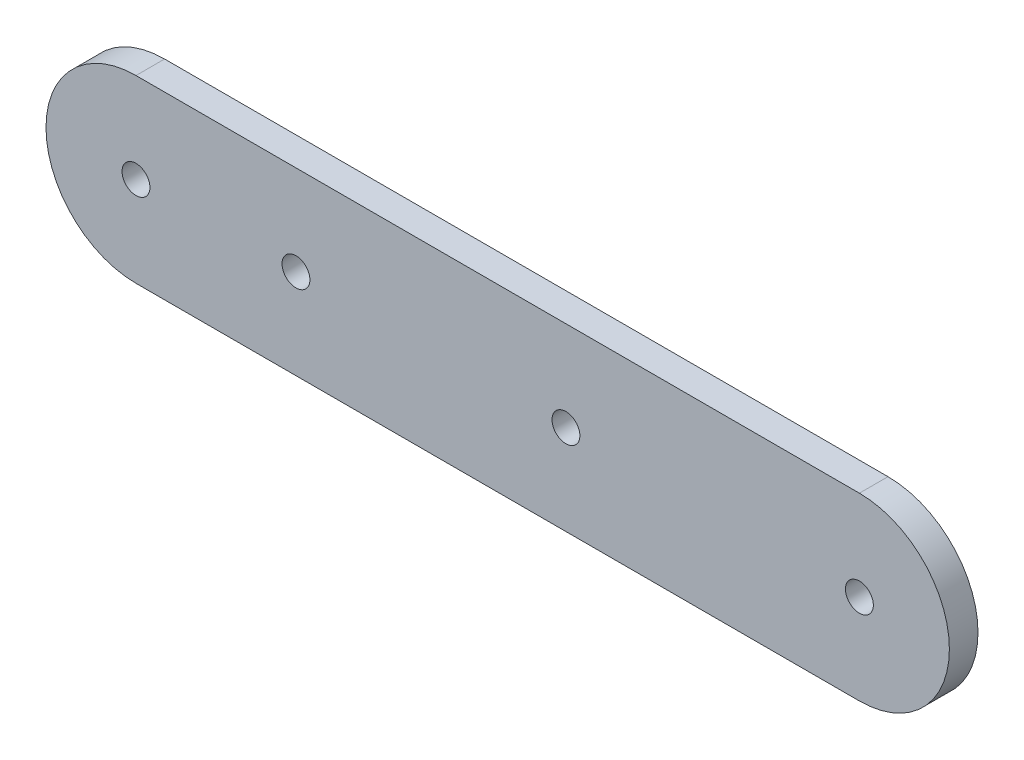
SolidWorks part; units mm, degrees
ref_plane "Front Plane" through (0, 0, 0) normal (0, 0, 1) x (1, 0, 0)
ref_plane "Top Plane" through (0, 0, 0) normal (0, 1, 0) x (1, 0, 0)
ref_plane "Right Plane" through (0, 0, 0) normal (1, 0, 0) x (0, 0, -1)
sketch "Sketch1" plane through (0, 0, 0) normal (0, 0, 1) x (1, 0, 0)
  line L0 (-34.978, 0) -> (34.978, 0) construction
  line L1 (-34.978, 10) -> (45.412, 10)
  line L2 (-34.978, -10) -> (45.412, -10)
  line L3 (45.412, -10) -> (45.412, 10) construction
  arc A0 (-34.978, 10) -> (-34.978, -10) centre (-34.978, 0) ccw
  arc A2 (45.412, -10) -> (45.412, 10) centre (0, 0) ccw
  point P2 (0, 0)
  dimension "D2" = 80.39
  dimension "D3" = 46.5
  dimension "D4" = 10
  dimension "D1" = 20
extrude "Boss-Extrude1" add sketch "Sketch1" along normal mid plane 3.18
sketch "Sketch6" plane through (0, 0, -1.59) normal (0, 0, -1) x (-1, 0, 0)
  line L0 (0, 0) -> (-23.3899, 0) construction
  circle A0 centre (-12.8, 0) radius 1.55
  arc A1 (-45.412, 10) -> (-45.412, -10) centre (0, 0) ccw construction
  dimension "D1" = 3.1
  dimension "D2" = 12.8
extrude "Cut-Extrude3" cut sketch "Sketch6" against normal through all and the other way through all
pattern_linear "LPattern3" count 3 spacing 30 along (-1, 0, 0) of "Cut-Extrude3"
sketch "Sketch7" plane through (0, 0, 1.59) normal (0, 0, 1) x (1, 0, 0)
  line L0 (0, 0) -> (57.5543, 0) construction
  line L1 (29.8, 0) -> (29.8, 14.5305) construction
  circle A1 centre (29.8, 3.5) radius 0.95
  circle A2 centre (29.8, -3.5) radius 0.95
  circle A3 centre (29.8, 0) radius 0.95
  circle A4 centre (12.8, 0) radius 1.55 construction
  dimension "D1" = 17
  dimension "D2" = 1.9
  dimension "D3" = 7
extrude "Cut-Extrude4" [suppressed] cut sketch "Sketch7" against normal through all
pattern_linear "LPattern4" [suppressed] count 2 spacing 14
sketch "Sketch8" [suppressed] plane through (0, 0, 1.59) normal (0, 0, 1) x (1, 0, 0)
  line L0 (36.8, 7) -> (36.8, 2.3742) construction
  line L1 (33.3, 7) -> (54.2454, 7) construction
  circle A0 centre (33.3, 7) radius 0.95
  circle A2 centre (40.3, 7) radius 0.95
  circle A3 centre (29.8, 3.5) radius 0.95 construction
  circle A4 centre (43.8, 3.5) radius 0.95 construction
  circle A5 centre (36.8, 7) radius 0.95
  dimension "D1" = 3.5
  dimension "D2" = 1.9
  dimension "D3" = 3.5
  dimension "D4" = 3.5
extrude "Cut-Extrude5" [suppressed] cut sketch "Sketch8" against normal through all
mirror "Mirror1" [suppressed] about plane through (0, 0, 0) normal (0, 1, 0)
mirror "Mirror2" [suppressed] about plane through (0, 0, 0) normal (1, 0, 0)
pattern_linear "LPattern5" [suppressed] count 2 spacing 116.18
sketch "Sketch22" plane through (0, 0, 0) normal (0, 0, 1) x (1, 0, 0)
  line L0 (45.412, 10) -> (45.412, -10)
  arc A0 (45.412, 10) -> (45.412, -10) centre (45.412, 0) cw
  arc A1 (45.412, -10) -> (45.412, 10) centre (0, 0) ccw
  dimension "D1" = 10
  dimension "D2" = 46.5
extrude "Boss-Extrude2" add sketch "Sketch22" along normal mid plane 3.18 contours A1 A0
sketch "Sketch11" plane through (0, 0, 1.59) normal (0, 0, 1) x (1, 0, 0)
  circle A1 centre (-96.958, 0) radius 1.55
  circle A2 centre (45.412, 0) radius 1.55
  dimension "D1" = 3.1
  dimension "D2" = 3.1
  dimension "D3" = 96.958
  dimension "D4" = 142.37
extrude "Cut-Extrude7" cut sketch "Sketch11" against normal through all
sketch "Sketch23" [suppressed] plane through (0, 0, 1.59) normal (0, 0, 1) x (1, 0, 0)
  line L0 (-110.588, 10) -> (-110.588, -10)
  line L1 (-110.588, -10) -> (45.412, -10) construction
  arc A1 (-110.588, 10) -> (-110.588, -10) centre (-110.588, 0) ccw
  arc A2 (-110.588, 10) -> (-110.588, -10) centre (-110.588, 0) ccw construction
sketch "Sketch26" [suppressed] plane through (0, 0, -1.59) normal (0, 0, -1) x (-1, 0, 0)
  line L0 (0, 0) -> (-52.9281, 0) construction
  line L1 (-36.8, 7) -> (-36.8, -7) construction
  circle A0 centre (-36.8, 0) radius 10.45
  dimension "D1" = 20.9
  dimension "D2" = 36.8
extrude "Cut-Extrude11" [suppressed] cut sketch "Sketch26" against normal through all
sketch "Sketch28" [suppressed] plane through (0, 0, -1.59) normal (0, 0, -1) x (-1, 0, 0)
  line L0 (-33.7664, 10) -> (-24.0675, 10)
  line L1 (-33.7664, 10) -> (41.098, 10) construction
  line L2 (-33.7664, -10) -> (-24.0675, -10)
  line L3 (41.098, -10) -> (-33.7664, -10) construction
  line L4 (-39.8336, 10) -> (-45.412, 10)
  line L5 (-45.412, -10) -> (-39.8336, -10)
  arc A0 (-24.0675, 10) -> (-24.0675, -10) centre (-36.8, 0) ccw
  arc A1 (-33.7664, -10) -> (-33.7664, 10) centre (-36.8, 0) ccw construction
  arc A4 (-45.412, 10) -> (-46.2947, 4.3651) centre (0, 0) ccw
  arc A5 (-33.7664, 10) -> (-39.8336, 10) centre (-36.8, 0) ccw
  arc A6 (-46.2947, -4.3651) -> (-45.412, -10) centre (0, 0) ccw
  arc A8 (-39.8336, -10) -> (-33.7664, -10) centre (-36.8, 0) ccw
  arc A9 (-46.2947, 4.3651) -> (-46.2947, -4.3651) centre (-36.8, 0) ccw
  dimension "D1" = 5.74
extrude "Boss-Extrude3" [suppressed] add sketch "Sketch28" against normal blind 3.18
sketch "Sketch29" [suppressed] plane through (0, 0, 1.59) normal (0, 0, 1) x (1, 0, 0)
  circle A0 centre (-41.098, 0) radius 1.55
  dimension "D1" = 3.1
extrude "Cut-Extrude12" [suppressed] cut sketch "Sketch29" against normal through all
sketch "Sketch30" [suppressed] plane through (0, 0, -1.59) normal (0, 0, -1) x (-1, 0, 0)
  circle A0 centre (41.098, 0) radius 1.55
  dimension "D1" = 3.1
extrude "Cut-Extrude13" [suppressed] cut sketch "Sketch30" against normal through all
sketch "Sketch31" plane through (0, 0, 1.59) normal (0, 0, 1) x (1, 0, 0)
  circle A0 centre (-34.978, 0) radius 1.55
  circle A1 centre (-17.2, 0) radius 1.55 construction
extrude "Cut-Extrude14" cut sketch "Sketch31" against normal through all
